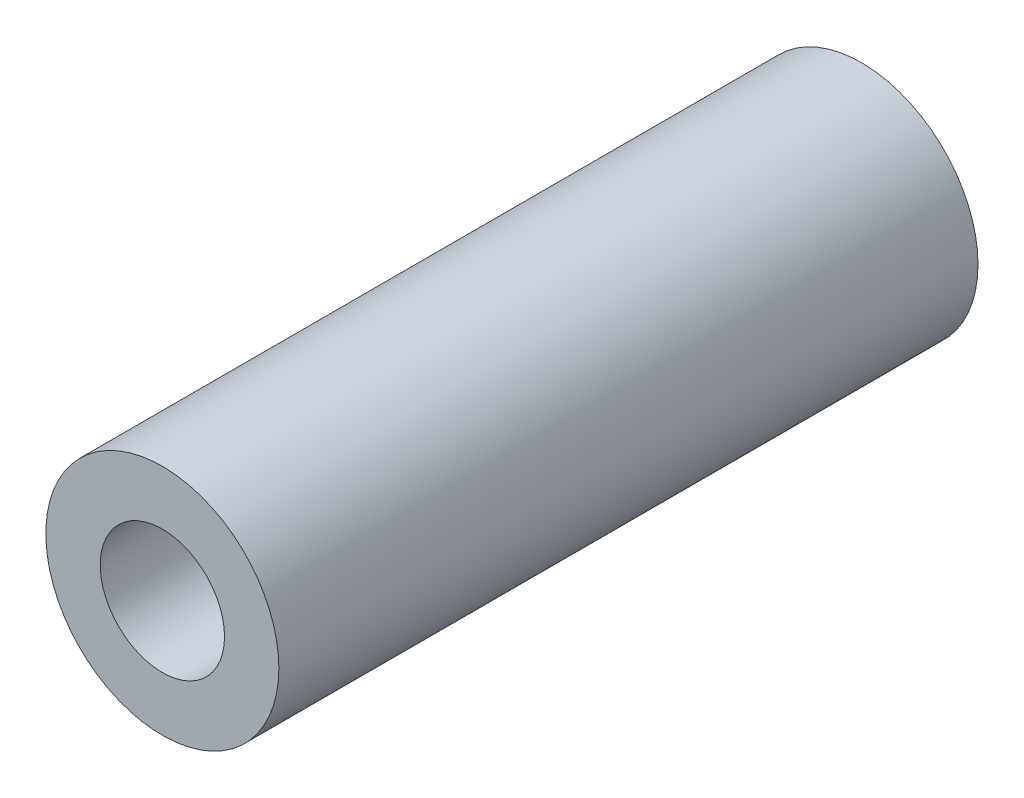
SolidWorks part; units mm, degrees
ref_plane "前视基准面" through (0, 0, 0) normal (0, 0, 1) x (1, 0, 0)
ref_plane "上视基准面" through (0, 0, 0) normal (0, 1, 0) x (1, 0, 0)
ref_plane "右视基准面" through (0, 0, 0) normal (1, 0, 0) x (0, 0, -1)
sketch "草图1" plane through (0, 0, 0) normal (0, 0, 1) x (1, 0, 0)
  circle A0 centre (0, 0) radius 1.6
  circle A1 centre (0, 0) radius 3
  dimension "D1" = 3.2
  dimension "D2" = 6
extrude "凸台-拉伸1" add sketch "草图1" along normal blind 18
